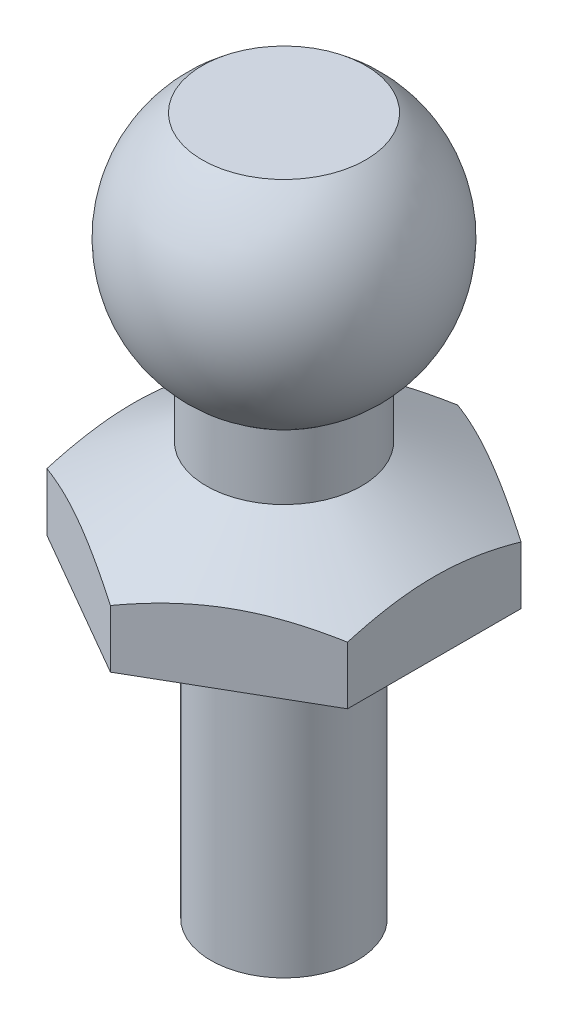
SolidWorks part; units mm, degrees
ref_plane "Front Plane" through (0, 0, 0) normal (0, 0, 1) x (1, 0, 0)
ref_plane "Top Plane" through (0, 0, 0) normal (0, 1, 0) x (1, 0, 0)
ref_plane "Right Plane" through (0, 0, 0) normal (1, 0, 0) x (0, 0, -1)
sketch "Sketch1" plane through (0, 0, 0) normal (0, 0, 1) x (1, 0, 0)
  line L0 (4.2311, 0) -> (1.2, 1.75)
  line L1 (1.2, 1.75) -> (1.2, 2.75)
  line L2 (1.2645, 6.15) -> (0, 6.15)
  line L3 (0, 0) -> (0, 6.15) construction
  line L4 (4.2311, 0) -> (0, 0)
  line L5 (0, 0) -> (0, 6.15)
  arc A0 (1.2, 2.75) -> (1.2645, 6.15) centre (0, 4.4734) ccw
  dimension "D5" = 2.1
  dimension "D1" = 1
  dimension "D2" = 1.75
  dimension "D3" = 120
  dimension "D4" = 3.4
  dimension "D6" = 2.4
revolve "Revolve1" add sketch "Sketch1" angle 360 about L3
sketch "Sketch2" plane through (0, 0, 0) normal (0, -1, 0) x (1, 0, 0)
  line L1 (0, 2.6847) -> (-2.325, 1.3423)
  line L2 (-2.325, 1.3423) -> (-2.325, -1.3423)
  line L3 (-2.325, -1.3423) -> (0, -2.6847)
  line L4 (0, -2.6847) -> (2.325, -1.3423)
  line L5 (2.325, -1.3423) -> (2.325, 1.3423)
  line L6 (2.325, 1.3423) -> (0, 2.6847)
  circle A0 centre (0, 0) radius 2.325 construction
  dimension "D1" = 4.65
extrude "Cut-Extrude1" cut sketch "Sketch2" against normal through all flip side to cut
sketch "Sketch3" plane through (0, 0, 0) normal (0, -1, 0) x (1, 0, 0)
  circle A0 centre (0, 0) radius 1.1303
  dimension "D1" = 2.2606
extrude "Boss-Extrude1" add sketch "Sketch3" along normal blind 4.64 contours A0
